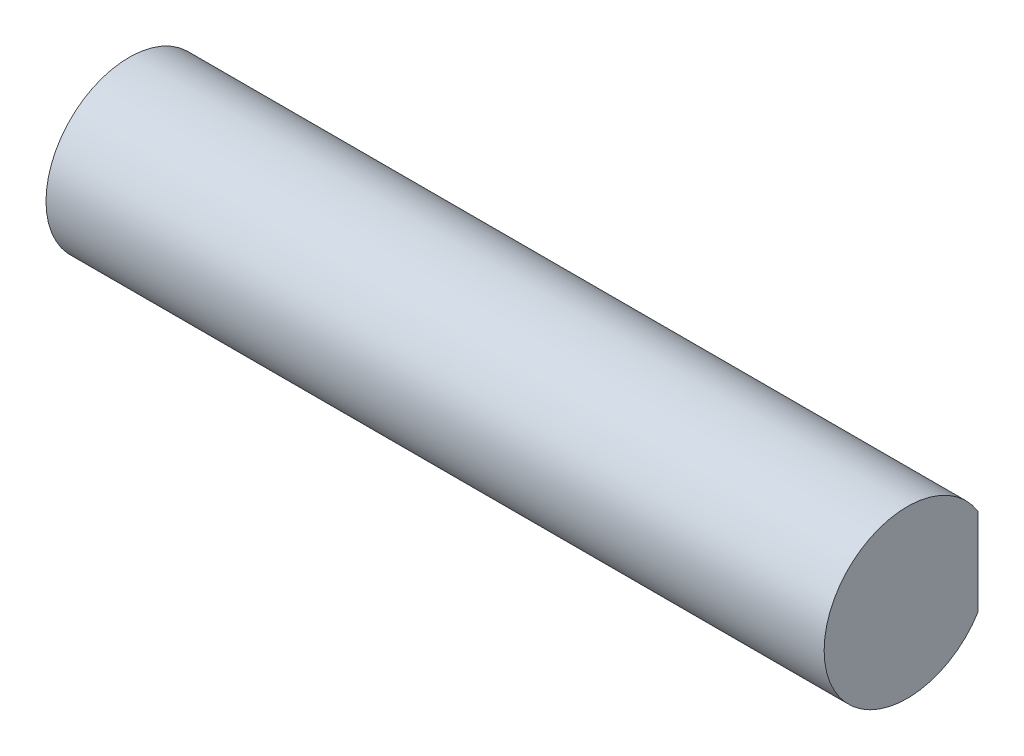
SolidWorks part; units mm, degrees
ref_plane "Front Plane" through (0, 0, 0) normal (0, 0, 1) x (1, 0, 0)
ref_plane "Top Plane" through (0, 0, 0) normal (0, 1, 0) x (1, 0, 0)
ref_plane "Right Plane" through (0, 0, 0) normal (1, 0, 0) x (0, 0, -1)
sketch "Sketch1" plane through (0, 0, 0) normal (1, 0, 0) x (0, 0, -1)
  circle A0 centre (0, 0) radius 2.35
  dimension "D1" = 4.7
extrude "Boss-Extrude1" add sketch "Sketch1" along normal blind 22
sketch "Sketch2" plane through (0, 0, 0) normal (-1, 0, 0) x (0, 0, 1)
  line L0 (-2, 1.2339) -> (-2, -1.2339)
  circle A0 centre (0, 0) radius 2.35 construction
  circle A1 centre (0, 0) radius 2.35
  arc A2 (-2, 1.2339) -> (-2, -1.2339) centre (0, 0) ccw
  dimension "D2" = 2
  dimension "D1" = 0
extrude "Cut-Extrude1" cut sketch "Sketch2" against normal up to surface (22 mm away) up to face at (22, 0, -2.35)
